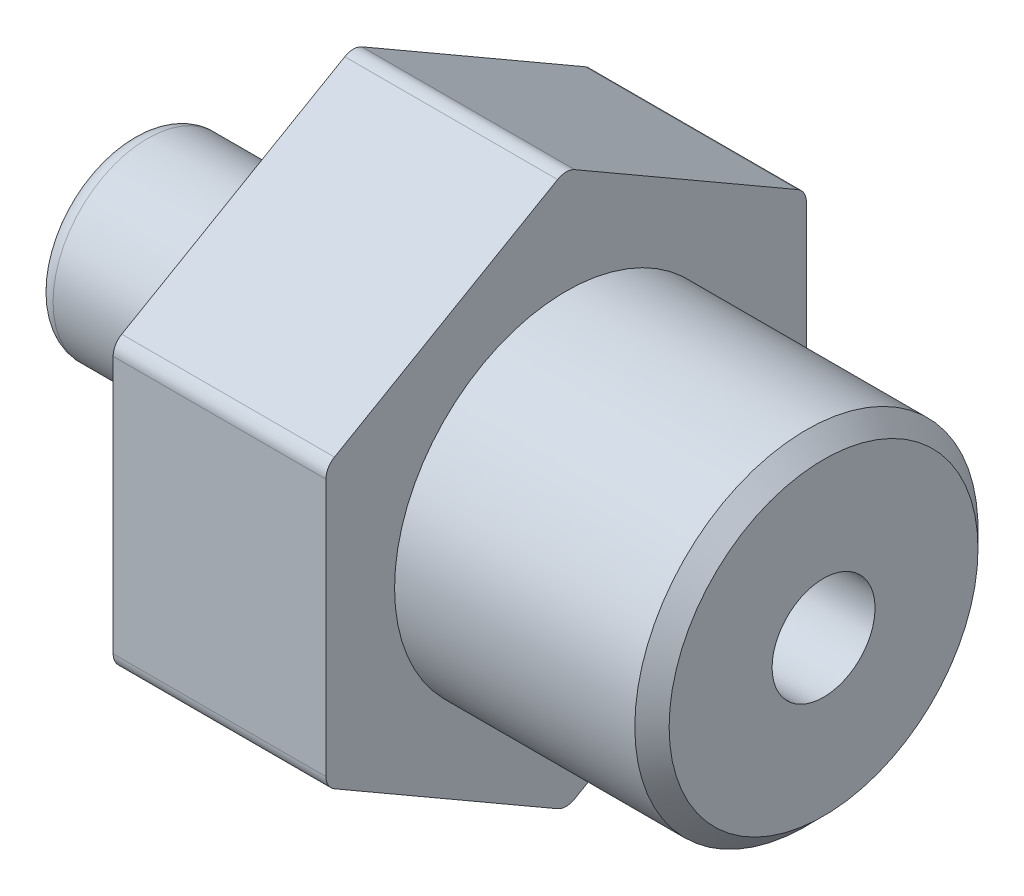
SolidWorks part; units mm, degrees
ref_plane "Спереди" through (0, 0, 0) normal (0, 0, 1) x (1, 0, 0)
ref_plane "Сверху" through (0, 0, 0) normal (0, 1, 0) x (1, 0, 0)
ref_plane "Справа" through (0, 0, 0) normal (1, 0, 0) x (0, 0, -1)
sketch "Эскиз1" plane through (0, 0, 0) normal (0, 0, 1) x (1, 0, 0)
  line L0 (0, 0) -> (7.5, 0) construction
  line L1 (7.5, 1.5) -> (7.5, 5)
  line L2 (7.5, 1.5) -> (0, 1.5)
  line L3 (7.5, 5) -> (0, 5)
  line L4 (0, 5) -> (0, 1.5)
  line L5 (0, 5) -> (0, 1.5)
  dimension "D1" = 7.5
  dimension "D2" = 5
  dimension "D3" = 1.5
  dimension "D4" = 7.5
revolve "Повернуть1" add sketch "Эскиз1" angle 360 about L0
sketch "Эскиз2" plane through (0, 0, 0) normal (-1, 0, 0) x (0, 0, 1)
  line L1 (0, 8.0829) -> (-7, 4.0415)
  line L2 (-7, 4.0415) -> (-7, -4.0415)
  line L3 (-7, -4.0415) -> (0, -8.0829)
  line L4 (0, -8.0829) -> (7, -4.0415)
  line L5 (7, -4.0415) -> (7, 4.0415)
  line L6 (7, 4.0415) -> (0, 8.0829)
  circle A0 centre (0, 0) radius 7 construction
  circle A1 centre (0, 0) radius 3
  dimension "D1" = 14
extrude "Бобышка-Вытянуть1" add sketch "Эскиз2" along normal blind 6.2
sketch "Эскиз3" plane through (-6.2, 0, 0) normal (-1, 0, 0) x (0, 0, 1)
  circle A0 centre (0, 0) radius 1.5
  circle A1 centre (0, 0) radius 2.75
  dimension "D1" = 3
  dimension "D2" = 5.5
extrude "Бобышка-Вытянуть2" add sketch "Эскиз3" along normal blind 6.5 separate body
fillet "Скругление2" radius 0.5 1 edges at (-12.7, 0, 2.75)
chamfer "Фаска1" distance 0.5 angle 45 1 edges at (7.5, 0, 5)
fillet "Скругление3" radius 0.5 6 edges at (-3.1, -4.0415, 7) (-3.1, 4.0415, 7) (-3.1, 8.0829, 0) (-3.1, 4.0415, -7) (-3.1, -4.0415, -7) (-3.1, -8.0829, 0)
